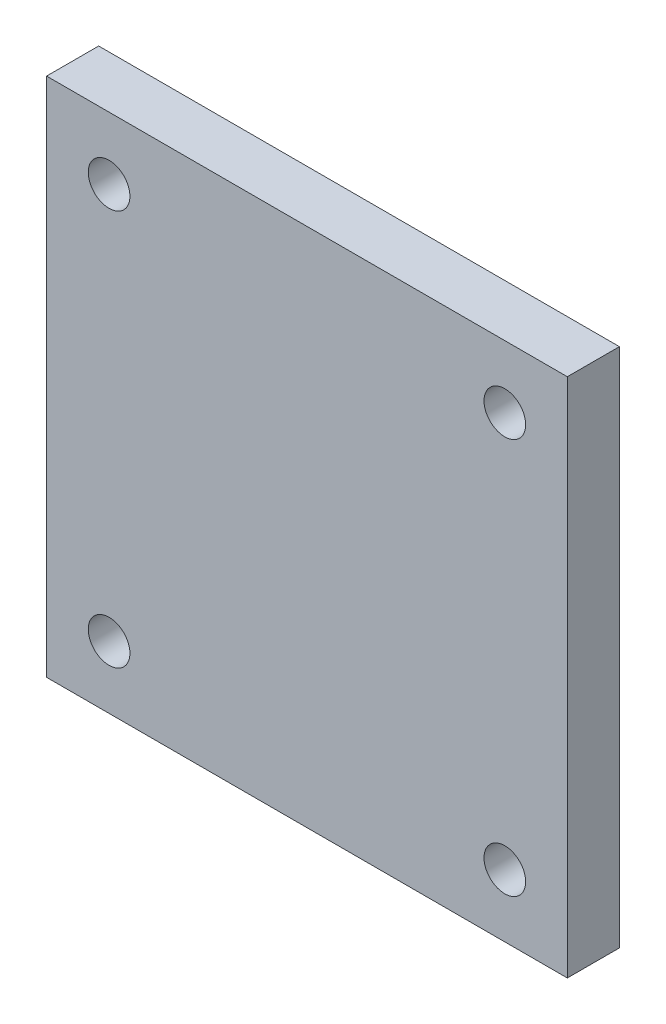
SolidWorks part; units mm, degrees
ref_plane "Plan de face" through (0, 0, 0) normal (0, 0, 1) x (1, 0, 0)
ref_plane "Plan de dessus" through (0, 0, 0) normal (0, 1, 0) x (1, 0, 0)
ref_plane "Plan de droite" through (0, 0, 0) normal (1, 0, 0) x (0, 0, -1)
sketch "Esquisse1" plane through (0, 0, 0) normal (0, 0, 1) x (1, 0, 0)
  line L1 (-25, 25) -> (25, 25)
  line L2 (-25, 25) -> (-25, -25)
  line L3 (-25, -25) -> (25, -25)
  line L4 (25, 25) -> (25, -25)
  line L5 (-25, 25) -> (25, -25) construction
  line L6 (-25, -25) -> (25, 25) construction
  point P0 (0, 0)
  dimension "D1" = 50
  dimension "D2" = 50
extrude "Boss.-Extru.1" add sketch "Esquisse1" along normal blind 5
sketch "Esquisse2" plane through (0, 0, 0) normal (0, 0, -1) x (-1, 0, 0)
  line L0 (25, 25) -> (25, -25) construction
  line L1 (-25, 25) -> (25, 25) construction
  line L3 (-25, -25) -> (-25, 25) construction
  line L4 (25, -25) -> (-25, -25) construction
  circle A0 centre (19, 19) radius 2
  circle A1 centre (-19, 19) radius 2
  circle A2 centre (-19, -19) radius 2
  circle A3 centre (19, -19) radius 2
  point P12 (0, 0)
  point P13 (0, 0)
  point P15 (-25, 16.5731)
  dimension "D3" = 4
  dimension "D6" = 4
  dimension "D7" = 4
  dimension "D10" = 4
  dimension "D1" = 6
  dimension "D2" = 6
  dimension "D4" = 6
  dimension "D5" = 6
  dimension "D8" = 6
  dimension "D9" = 6
  dimension "D11" = 6
  dimension "D12" = 6
extrude "Enlèv. mat.-Extru.1" cut sketch "Esquisse2" against normal blind 10
